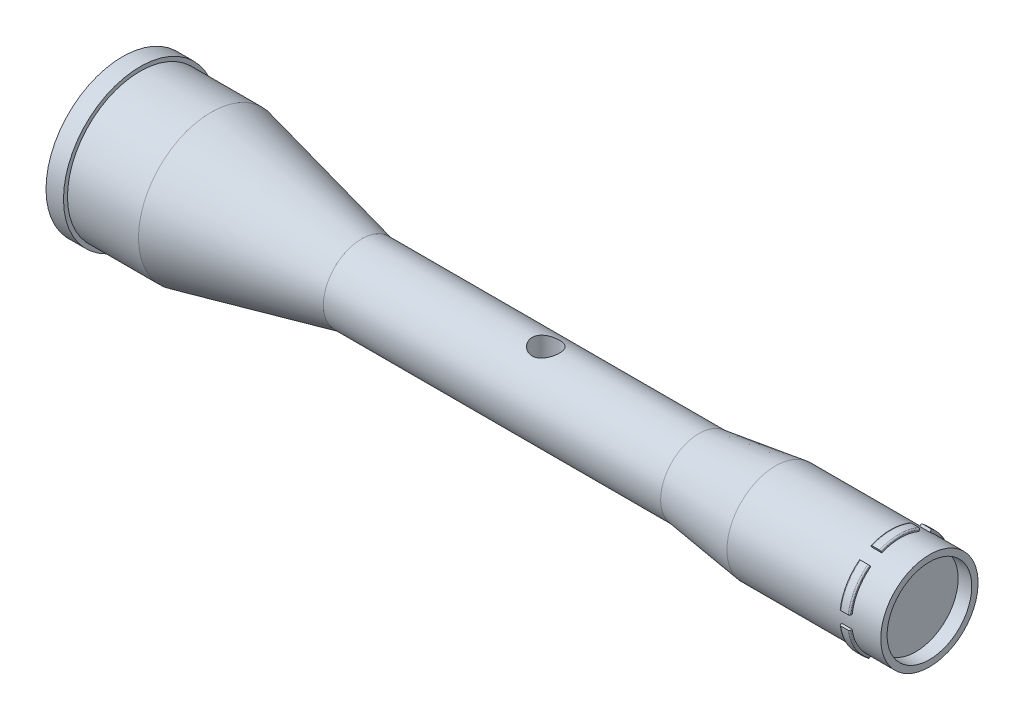
SolidWorks part; units mm, degrees
ref_plane "Front Plane" through (0, 0, 0) normal (0, 0, 1) x (1, 0, 0)
ref_plane "Top Plane" through (0, 0, 0) normal (0, 1, 0) x (1, 0, 0)
ref_plane "Right Plane" through (0, 0, 0) normal (1, 0, 0) x (0, 0, -1)
sketch "Sketch1" plane through (0, 0, 0) normal (0, 1, 0) x (1, 0, 0)
  line L0 (-147.75, 0) -> (147.75, 0) construction
  line L1 (-147.75, 0) -> (-147.75, 28.025)
  line L2 (-60.19, 14) -> (63.31, 14)
  line L3 (-147.75, 28.025) -> (-141.35, 28.025)
  line L4 (-141.35, 28.025) -> (-141.35, 26.56)
  line L5 (-141.35, 26.56) -> (-115.35, 26.56)
  line L6 (147.75, 0) -> (147.75, 17.82)
  line L7 (147.75, 17.82) -> (91.41, 17.82)
  line L8 (-60.19, 14) -> (-115.35, 26.56)
  line L9 (63.31, 14) -> (91.41, 17.82)
  line L10 (-147.75, 0) -> (147.75, 0)
  point P3 (0, 0)
  dimension "D1" = 295.5
  dimension "D2" = 28
  dimension "D3" = 123.5
  dimension "D4" = 6.4
  dimension "D5" = 28.025
  dimension "D6" = 26.56
  dimension "D7" = 26
  dimension "D8" = 35.64
  dimension "D9" = 28.1
  dimension "D10" = 55.16
revolve "Revolve1" add sketch "Sketch1" angle 360 about L0
ref_plane "Plane1" through (137.11, 0, 0) normal (1, 0, 0) x (0, 0, -1)
sketch "Sketch2" plane through (137.11, 0, 0) normal (1, 0, 0) x (0, 0, -1)
  line L0 (0, 0) -> (-7.1753, 17.3227)
  line L1 (0, 0) -> (7.1753, 17.3227)
  line L2 (0, 0) -> (0, 18.75) construction
  line L3 (0, 0) -> (11.4143, 14.8754)
  line L4 (0, 0) -> (18.5896, 2.4474)
  line L5 (0, 0) -> (18.5896, -2.4474)
  line L6 (0, 0) -> (11.4143, -14.8754)
  line L7 (0, 0) -> (7.1753, -17.3227)
  line L8 (0, 0) -> (-7.1753, -17.3227)
  line L9 (0, 0) -> (-11.4143, -14.8754)
  line L10 (0, 0) -> (-18.5896, -2.4474)
  line L11 (0, 0) -> (-18.5896, 2.4474)
  line L12 (0, 0) -> (-11.4143, 14.8754)
  circle A0 centre (0, 0) radius 17.82 construction
  circle A1 centre (0, 0) radius 17.82
  circle A2 centre (0, 0) radius 18.75
  point P19 (0, 0)
  dimension "D1" = 37.5
  dimension "D2" = 45
  dimension "D3" = 22.5
  dimension "D4" = 6
extrude "Boss-Extrude1" add sketch "Sketch2" against normal blind 3.73 separate body contours L2 A1 L1 A2 | A1 L2 A2 L0 | L4 A2 L3 A1 | L6 A2 L5 A1 | L8 A2 L7 A1 | L10 A2 L9 A1 | L12 A2 L11 A1
fillet "Fillet1" radius 0.5 2 edges at (133.38, 9.375, -16.238) (137.11, 9.375, -16.238)
fillet "Fillet2" radius 0.5 2 edges at (133.38, 18.75, 0) (137.11, 18.75, 0)
fillet "Fillet3" radius 0.5 2 edges at (133.38, 9.375, 16.238) (137.11, 9.375, 16.238)
fillet "Fillet4" radius 0.5 2 edges at (133.38, -9.375, 16.238) (137.11, -9.375, 16.238)
fillet "Fillet5" radius 0.5 2 edges at (137.11, -18.75, 0) (133.38, -18.75, 0)
fillet "Fillet6" radius 0.5 2 edges at (137.11, -9.375, -16.238) (133.38, -9.375, -16.238)
sketch "Sketch3" plane through (0, 0, 0) normal (0, 1, 0) x (1, 0, 0)
  line L0 (63.31, -14) -> (63.31, 14) construction
  circle A0 centre (7.27, 0) radius 5
  dimension "D2" = 10
  dimension "D1" = 56.04
extrude "Cut-Extrude1" cut sketch "Sketch3" against normal through all both and the other way through all
sketch "Sketch4" plane through (-147.75, 0, 0) normal (-1, 0, 0) x (0, 0, 1)
  circle A0 centre (0, 0) radius 25.25
  dimension "D1" = 50.5
extrude "Cut-Extrude2" cut sketch "Sketch4" against normal blind 5
sketch "Sketch5" plane through (147.75, 0, 0) normal (1, 0, 0) x (0, 0, -1)
  circle A0 centre (0, 0) radius 15.5
  dimension "D1" = 31
extrude "Cut-Extrude3" cut sketch "Sketch5" against normal blind 5
sketch "Sketch7" plane through (0, 0, 0) normal (0, 0, 1) x (1, 0, 0)
  line L0 (-142.75, 25.25) -> (-142.75, -25.25) construction
  line L1 (-142.75, -25.25) -> (-142.75, 0)
  line L2 (-142.75, 25.25) -> (-142.75, -25.25) construction
  line L3 (-147.75, -25.25) -> (-142.75, -25.25) construction
  line L4 (-142.75, 0) -> (-152.75, 0)
  arc A0 (-142.75, -25.25) -> (-152.75, 0) centre (-115.8719, 0) cw
  dimension "D1" = 10
revolve "Revolve3" add sketch "Sketch7" angle 360 about L4
